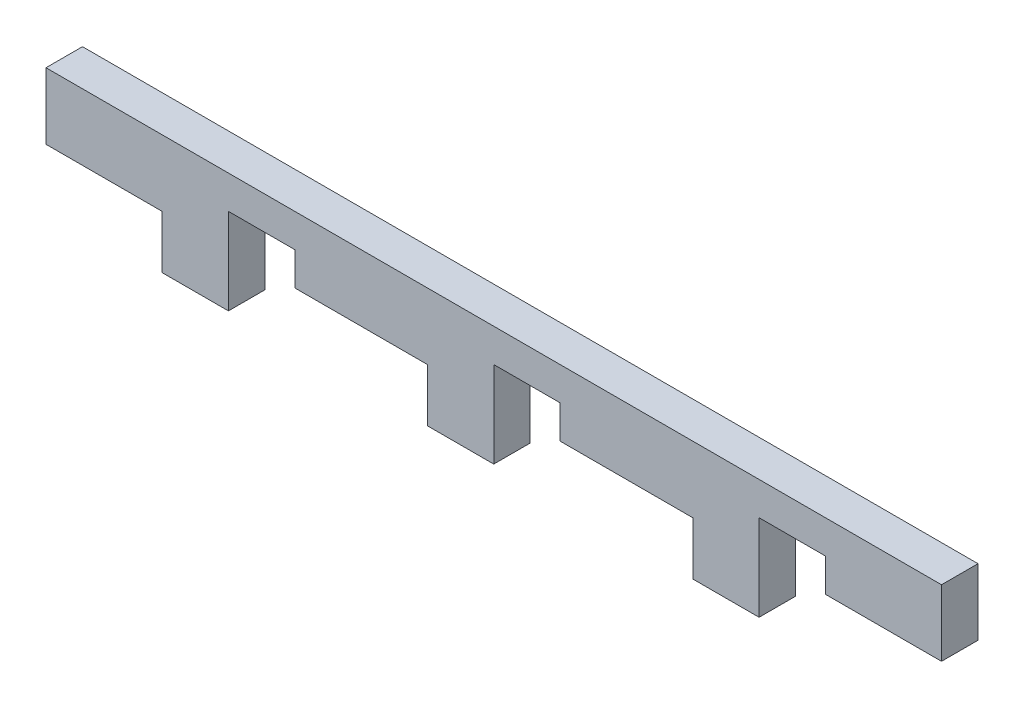
SolidWorks part; units mm, degrees
ref_plane "前视基准面" through (0, 0, 0) normal (0, 0, 1) x (1, 0, 0)
ref_plane "上视基准面" through (0, 0, 0) normal (0, 1, 0) x (1, 0, 0)
ref_plane "右视基准面" through (0, 0, 0) normal (1, 0, 0) x (0, 0, -1)
sketch "草图1" plane through (0, 0, 0) normal (0, 0, 1) x (1, 0, 0)
  line L2 (-67.5, -10) -> (-67.5, 0)
  line L3 (-67.5, 0) -> (67.5, 0)
  line L4 (67.5, -10) -> (67.5, 0)
  line L7 (-10, -10) -> (-30, -10)
  line L9 (-50, -10) -> (-67.5, -10)
  line L10 (10, -10) -> (30, -10)
  line L12 (50, -10) -> (67.5, -10)
  line L13 (-50, -10) -> (-50, -18)
  line L14 (-50, -18) -> (-40, -18)
  line L15 (-40, -18) -> (-40, -5)
  line L16 (-40, -5) -> (-30, -5)
  line L17 (-30, -5) -> (-30, -10)
  line L18 (-10, -10) -> (-10, -18)
  line L19 (-10, -18) -> (0, -18)
  line L20 (0, -18) -> (0, -5)
  line L21 (0, -5) -> (10, -5)
  line L22 (10, -5) -> (10, -10)
  line L23 (30, -10) -> (30, -18)
  line L24 (30, -18) -> (40, -18)
  line L25 (40, -18) -> (40, -5)
  line L26 (40, -5) -> (50, -5)
  line L27 (50, -5) -> (50, -10)
  point P0 (0, 0)
  point P9 (0, -10)
extrude "凸台-拉伸1" add sketch "草图1" along normal blind 5.5
